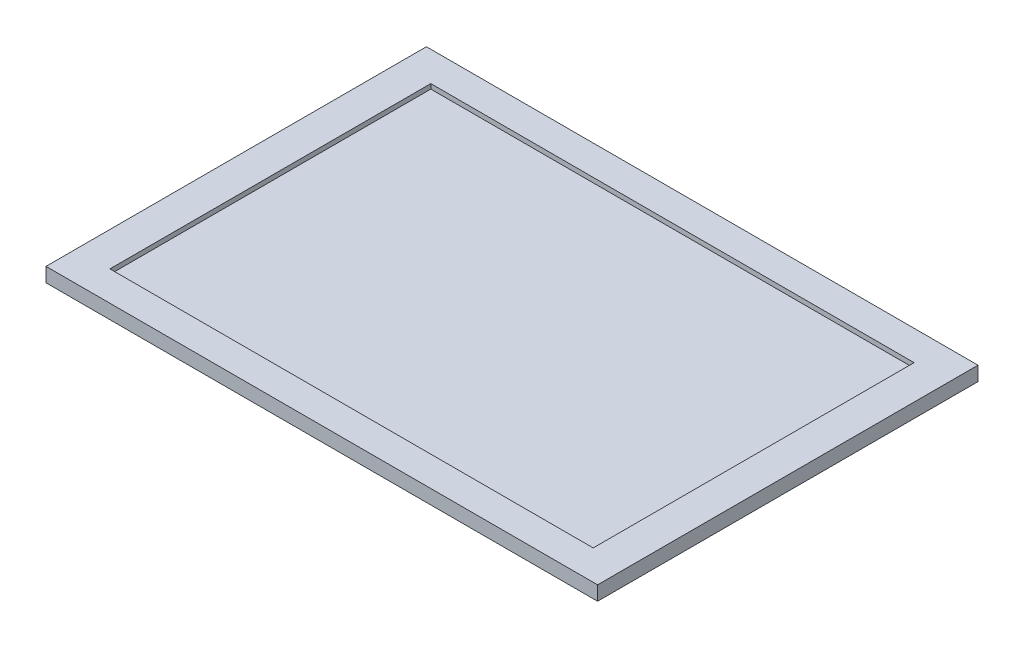
SolidWorks part; units mm, degrees
ref_plane "Front Plane" through (0, 0, 0) normal (0, 0, 1) x (1, 0, 0)
ref_plane "Top Plane" through (0, 0, 0) normal (0, 1, 0) x (1, 0, 0)
ref_plane "Right Plane" through (0, 0, 0) normal (1, 0, 0) x (0, 0, -1)
sketch "Sketch1" plane through (0, 0, 0) normal (0, 1, 0) x (1, 0, 0)
  line L1 (-147.32, -101.6) -> (147.32, -101.6)
  line L2 (-147.32, -101.6) -> (-147.32, 101.6)
  line L3 (-147.32, 101.6) -> (147.32, 101.6)
  line L4 (147.32, -101.6) -> (147.32, 101.6)
  line L5 (-147.32, -101.6) -> (147.32, 101.6) construction
  line L6 (-147.32, 101.6) -> (147.32, -101.6) construction
  point P0 (0, 0)
  dimension "D1" = 294.64
  dimension "D2" = 203.2
extrude "Boss-Extrude1" add sketch "Sketch1" along normal blind 7.62
sketch "Sketch2" plane through (0, 7.62, 0) normal (0, 1, 0) x (1, 0, 0)
  line L0 (0, 101.6) -> (0, -101.6) construction
  line L1 (147.32, 101.6) -> (-147.32, 101.6) construction
  line L2 (-147.32, -101.6) -> (147.32, -101.6) construction
  line L3 (-147.32, 0) -> (147.32, 0) construction
  line L4 (-147.32, 101.6) -> (-147.32, -101.6) construction
  line L5 (147.32, -101.6) -> (147.32, 101.6) construction
  line L7 (-129.0776, -85.7052) -> (129.0776, -85.7052)
  line L8 (-129.0776, -85.7052) -> (-129.0776, 85.7052)
  line L9 (-129.0776, 85.7052) -> (129.0776, 85.7052)
  line L10 (129.0776, -85.7052) -> (129.0776, 85.7052)
  line L11 (-129.0776, -85.7052) -> (129.0776, 85.7052) construction
  line L12 (-129.0776, 85.7052) -> (129.0776, -85.7052) construction
  point P12 (0, 0)
  dimension "D1" = 309.88
extrude "Cut-Extrude1" cut sketch "Sketch2" against normal blind 2.54
